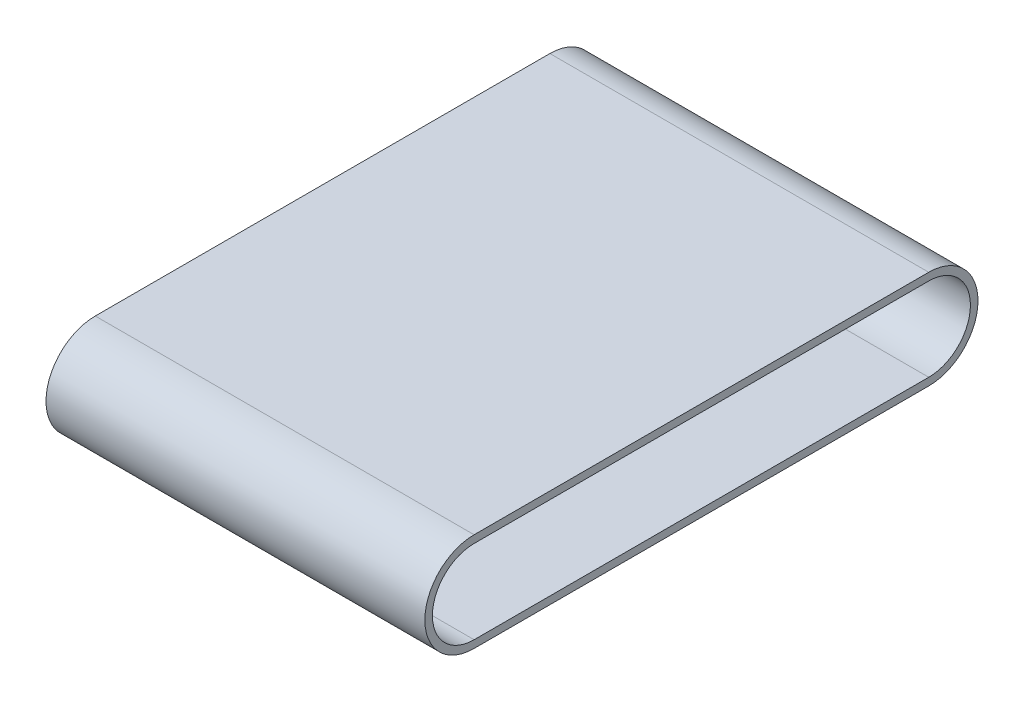
SolidWorks part; units mm, degrees
ref_plane "Front Plane" through (0, 0, 0) normal (0, 0, 1) x (1, 0, 0)
ref_plane "Top Plane" through (0, 0, 0) normal (0, 1, 0) x (1, 0, 0)
ref_plane "Right Plane" through (0, 0, 0) normal (1, 0, 0) x (0, 0, -1)
sketch "Sketch1" plane through (0, 0, 0) normal (1, 0, 0) x (0, 0, -1)
  line L0 (-183.6787, 35.8481) -> (-63.6787, 35.8481)
  line L1 (-183.6787, 35.8481) -> (-183.6787, 9.8481) construction
  line L2 (-123.6787, 35.8481) -> (-123.6787, -19.5304) construction
  line L3 (-183.6787, 9.8481) -> (-63.6787, 9.8481)
  line L4 (-183.6787, 11.8481) -> (-63.6787, 11.8481)
  line L5 (-183.6787, 33.8481) -> (-63.6787, 33.8481)
  arc A0 (-183.6787, 35.8481) -> (-183.6787, 9.8481) centre (-183.6787, 22.8481) ccw
  arc A1 (-63.6787, 35.8481) -> (-63.6787, 9.8481) centre (-63.6787, 22.8481) cw
  arc A2 (-183.6787, 33.8481) -> (-183.6787, 11.8481) centre (-183.6787, 22.8481) ccw
  arc A3 (-63.6787, 33.8481) -> (-63.6787, 11.8481) centre (-63.6787, 22.8481) cw
  dimension "D1" = 120
  dimension "D2" = 26
  dimension "D3" = 2
extrude "Boss-Extrude1" add sketch "Sketch1" along normal blind 100
